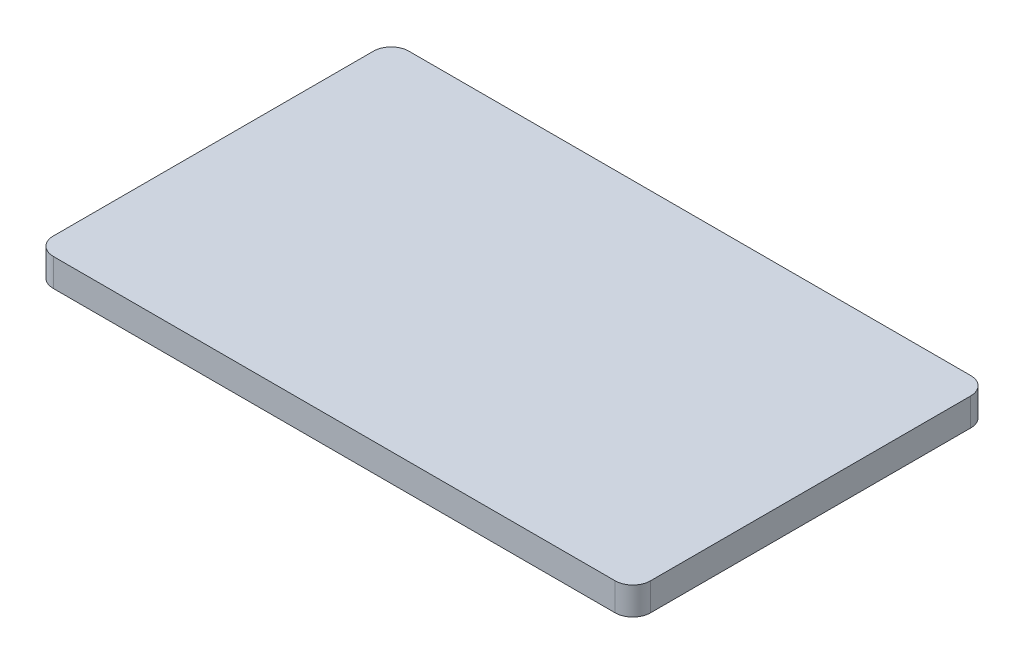
SolidWorks part; units mm, degrees
ref_plane "Front Plane" through (0, 0, 0) normal (0, 0, 1) x (1, 0, 0)
ref_plane "Top Plane" through (0, 0, 0) normal (0, 1, 0) x (1, 0, 0)
ref_plane "Right Plane" through (0, 0, 0) normal (1, 0, 0) x (0, 0, -1)
sketch "Sketch1" plane through (0, 0, 0) normal (0, 1, 0) x (1, 0, 0)
  line L1 (-107.5, -64) -> (107.5, -64)
  line L2 (-107.5, -64) -> (-107.5, 64)
  line L3 (-107.5, 64) -> (107.5, 64)
  line L4 (107.5, -64) -> (107.5, 64)
  line L5 (-107.5, -64) -> (107.5, 64) construction
  line L6 (-107.5, 64) -> (107.5, -64) construction
  point P0 (0, 0)
  dimension "D1" = 215
  dimension "D2" = 128
extrude "Boss-Extrude1" add sketch "Sketch1" along normal blind 10
fillet "Fillet1" radius 6.35 4 edges at (-107.5, 5, -64) (-107.5, 5, 64) (107.5, 5, 64) (107.5, 5, -64)
